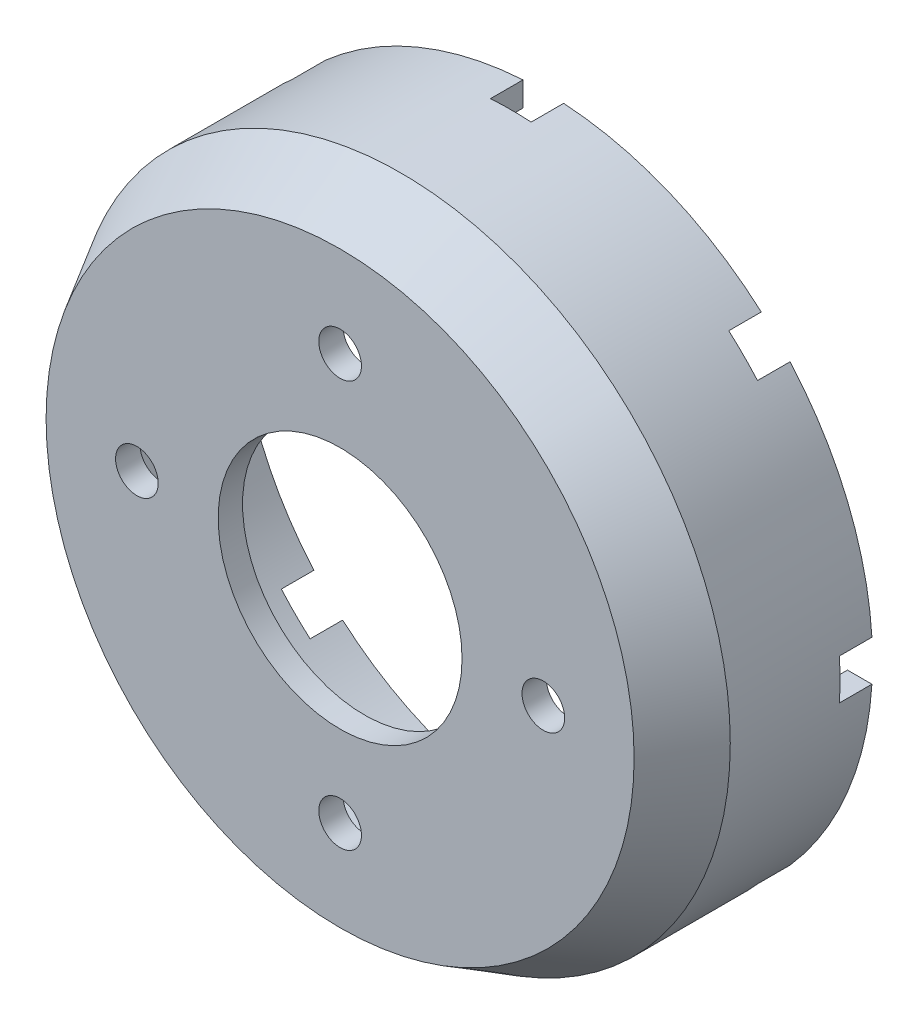
SolidWorks part; units mm, degrees
ref_plane "Płaszczyzna przednia" through (0, 0, 0) normal (0, 0, 1) x (1, 0, 0)
ref_plane "Płaszczyzna górna" through (0, 0, 0) normal (0, 1, 0) x (1, 0, 0)
ref_plane "Płaszczyzna prawa" through (0, 0, 0) normal (1, 0, 0) x (0, 0, -1)
sketch "Szkic1" plane through (0, 0, 0) normal (0, 0, 1) x (1, 0, 0)
  circle A0 centre (0, 0) radius 81
  dimension "D1" = 162
extrude "Dodanie-wyciągnięcie1" add sketch "Szkic1" along normal blind 50
shell "Skorupa1" thickness 6
sketch "Szkic2" plane through (0, 0, 0) normal (0, 0, -1) x (-1, 0, 0)
  line L5 (5, 85.8545) -> (5, 69.8212)
  line L6 (-5, 69.8212) -> (-5, 85.8545)
  circle A1 centre (0, 0) radius 86
  circle A2 centre (0, 0) radius 70
  circle A3 centre (0, 0) radius 75 construction
  circle A4 centre (0, 0) radius 81 construction
  circle M10 centre (0, 0) radius 75
  circle M11 centre (0, 0) radius 81
  dimension "D1" = 5
  dimension "D2" = 5
  dimension "D3" = 10
  dimension "D4" = 5
extrude "Wytnij-wyciągnięcie1" cut sketch "Szkic2" against normal blind 8 contours L5 A1 L6 M11 | L6 L5 M10 M11 | A2 L5 L6 M10
pattern_circular "Szyk kołowy1" count 8 over 360 about axis through (0, 0, 0) along (0, 0, 1) of "Wytnij-wyciągnięcie1"
sketch "Szkic5" plane through (0, 0, 50) normal (0, 0, 1) x (1, 0, 0)
  circle A0 centre (0, 0) radius 30
  circle A1 centre (0, 50) radius 5.25
  circle A2 centre (50, 0) radius 5.25
  circle A3 centre (0, -50) radius 5.25
  circle A4 centre (-50, 0) radius 5.25
  dimension "D1" = 60
  dimension "D3" = 10.5
  dimension "D2" = 50
  dimension "D4" = 4
extrude "Wytnij-wyciągnięcie2" cut sketch "Szkic5" against normal up to surface (6 mm away) up to face at (75, 0, 44)
sketch "Szkic6" plane through (0, 0, 0) normal (0, 0, -1) x (-1, 0, 0)
  line L1 (0, 0) -> (0, 107.389) construction
  line L2 (0, 0) -> (-43.4637, 104.9306) construction
  line L4 (-5, 74.8331) -> (-5, 80.8455) construction
  line L5 (-53.6309, 60.702) -> (-49.3795, 56.4506) construction
  line L6 (-53.6309, 60.702) -> (-49.3795, 56.4506)
  line L7 (-5, 74.8331) -> (-5, 80.8455)
  circle A0 centre (-29.8493, 72.0626) radius 1.5
  circle A1 centre (0, 0) radius 78 construction
  dimension "D1" = 3
  dimension "D2" = 156
  dimension "D3" = 22.5
extrude "Wytnij-wyciągnięcie3" cut sketch "Szkic6" against normal blind 10 contours A0
pattern_circular "Szyk kołowy2" count 8 over 360 about axis through (0, 0, 0) along (0, 0, 1) of "Wytnij-wyciągnięcie3"
chamfer "Sfazowanie1" distance 15 angle 30 1 edges at (75, 0, 44)
chamfer "Sfazowanie2" distance 15 angle 30 1 edges at (81, 0, 50)
equation "\"D4@Szkic2\"=\"D3@Szkic2\"/2"
equation "\"D2@Szkic6\"=78*2"
